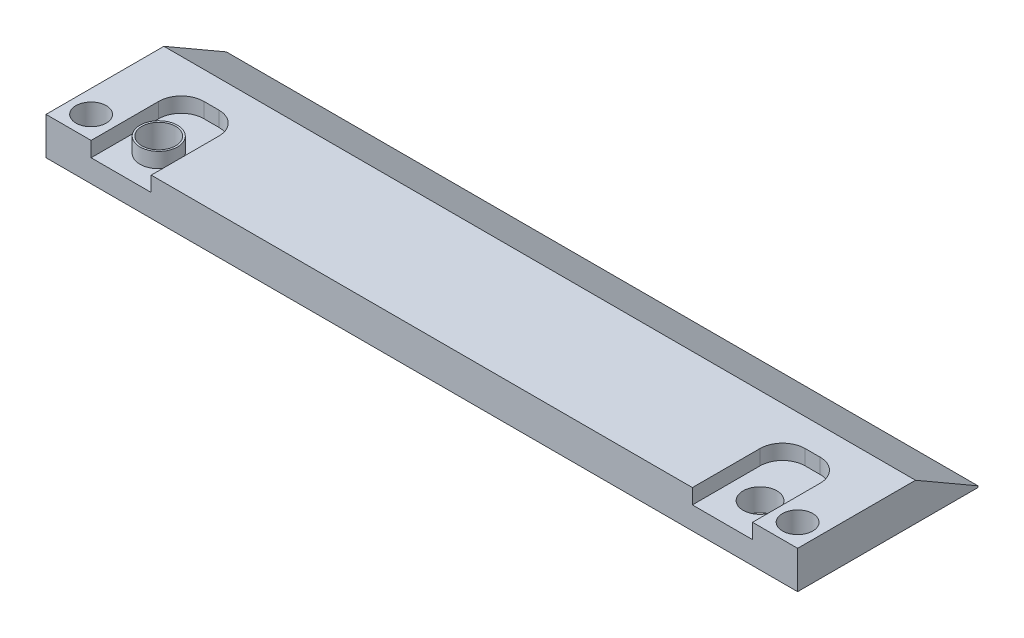
SolidWorks part; units mm, degrees
ref_plane "Alzado" through (0, 0, 0) normal (0, 0, 1) x (1, 0, 0)
ref_plane "Planta" through (0, 0, 0) normal (0, 1, 0) x (1, 0, 0)
ref_plane "Vista lateral" through (0, 0, 0) normal (1, 0, 0) x (0, 0, -1)
sketch "Croquis1" plane through (0, 0, 0) normal (0, 1, 0) x (1, 0, 0)
  line L0 (-44, -12) -> (-44, 0)
  line L1 (-50, 12) -> (50, 12)
  line L2 (-50, 12) -> (-50, -12)
  line L3 (-50, -12) -> (50, -12)
  line L4 (50, 12) -> (50, -12)
  line L5 (-50, 12) -> (50, -12) construction
  line L6 (-50, -12) -> (50, 12) construction
  line L7 (-44, 0) -> (-36, 0)
  line L8 (-36, 0) -> (-36, -12)
  line L9 (0, 0) -> (0, -6.9349) construction
  line L10 (36, 0) -> (36, -12)
  line L12 (44, -12) -> (44, 0)
  circle A0 centre (-47, -9) radius 2.0175
  circle A1 centre (-40, -7) radius 2.25
  circle A2 centre (40, -7) radius 2.25
  circle A3 centre (47, -9) radius 2.0175
  point P0 (0, 0)
  dimension "D9" = 4.5
  dimension "D1" = 24
  dimension "D2" = 100
  dimension "D3" = 3
  dimension "D4" = 3
  dimension "D5" = 6
  dimension "D6" = 8
  dimension "D7" = 12
  dimension "D8" = 2
extrude "Saliente-Extruir1" add sketch "Croquis1" along normal blind 5
sketch "Croquis2" plane through (0, 5, 0) normal (0, 1, 0) x (1, 0, 0)
  line L0 (-50, -12) -> (50, -12) construction
  line L2 (-44, -3) -> (-44, -12)
  line L3 (-44, -12) -> (-36, -12)
  line L4 (-36, -3) -> (-36, -12)
  line L5 (0, 0) -> (0, -5.1087) construction
  line L6 (41, 0) -> (39, 0)
  line L7 (-41, 0) -> (-39, 0)
  line L8 (36, -3) -> (36, -12)
  line L9 (44, -12) -> (36, -12)
  line L10 (44, -3) -> (44, -12)
  arc A0 (-39, 0) -> (-36, -3) centre (-39, -3) cw
  arc A1 (-41, 0) -> (-44, -3) centre (-41, -3) ccw
  arc A2 (39, 0) -> (36, -3) centre (39, -3) ccw
  arc A3 (41, 0) -> (44, -3) centre (41, -3) cw
  circle A4 centre (-40, -7) radius 2.5
  point P0 (-40, -7)
  point P15 (40, -7)
  point P18 (-36, 0)
  point P21 (-44, 0)
  dimension "D3" = 3
  dimension "D4" = 5
  dimension "D1" = 8
  dimension "D2" = 4
extrude "Cortar-Extruir1" cut sketch "Croquis2" against normal blind 2
sketch "Croquis3" plane through (-50, 0, 0) normal (-1, 0, 0) x (0, 0, 1)
  line L0 (-12, 0) -> (-12, 0.2)
  line L1 (-12, 5) -> (-12, 0) construction
  line L2 (-12, 0.2) -> (-6.1009, 3.6058)
  line L3 (-12, 0) -> (-5.7905, 0)
  line L4 (-12, 0) -> (12, 0) construction
  line L5 (-6.1009, 3.6058) -> (-3.0399, 5.3731)
  line L6 (-3.0399, 5.3731) -> (-12.7572, 5.3731)
  line L7 (-12.7572, 5.3731) -> (-12.7572, 0.2)
  line L8 (-12.7572, 0.2) -> (-12, 0.2)
  line M10 (12, 5) -> (-12, 5)
  line M11 (-12, 5) -> (-12, 0)
  dimension "D1" = 0.2
  dimension "D2" = 30
extrude "Cortar-Extruir5" cut sketch "Croquis3" against normal blind 141 contours L2 L5 M10 M11 | L7 L8 L5 L6 M11 M10
